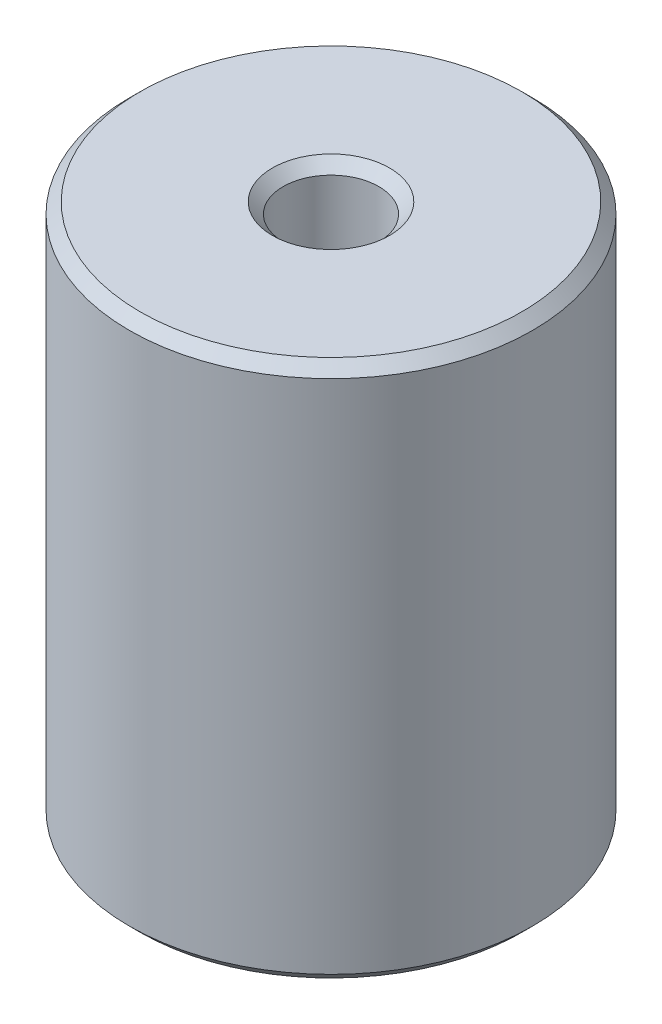
SolidWorks part; units mm, degrees
ref_plane "Front Plane" through (0, 0, 0) normal (0, 0, 1) x (1, 0, 0)
ref_plane "Top Plane" through (0, 0, 0) normal (0, 1, 0) x (1, 0, 0)
ref_plane "Right Plane" through (0, 0, 0) normal (1, 0, 0) x (0, 0, -1)
sketch "Sketch1" plane through (0, 0, 0) normal (0, 1, 0) x (1, 0, 0)
  circle A0 centre (0, 0) radius 1.1303
  circle A1 centre (0, 0) radius 4.7625
  dimension "D1" = 2.2606
  dimension "D2" = 9.525
extrude "Boss-Extrude1" add sketch "Sketch1" along normal blind 12.7
chamfer "Chamfer1" distance 0.254 angle 45 4 edges at (0, 0, 1.1303) (0, 0, 4.7625) (0, 12.7, 1.1303) (0, 12.7, 4.7625)
